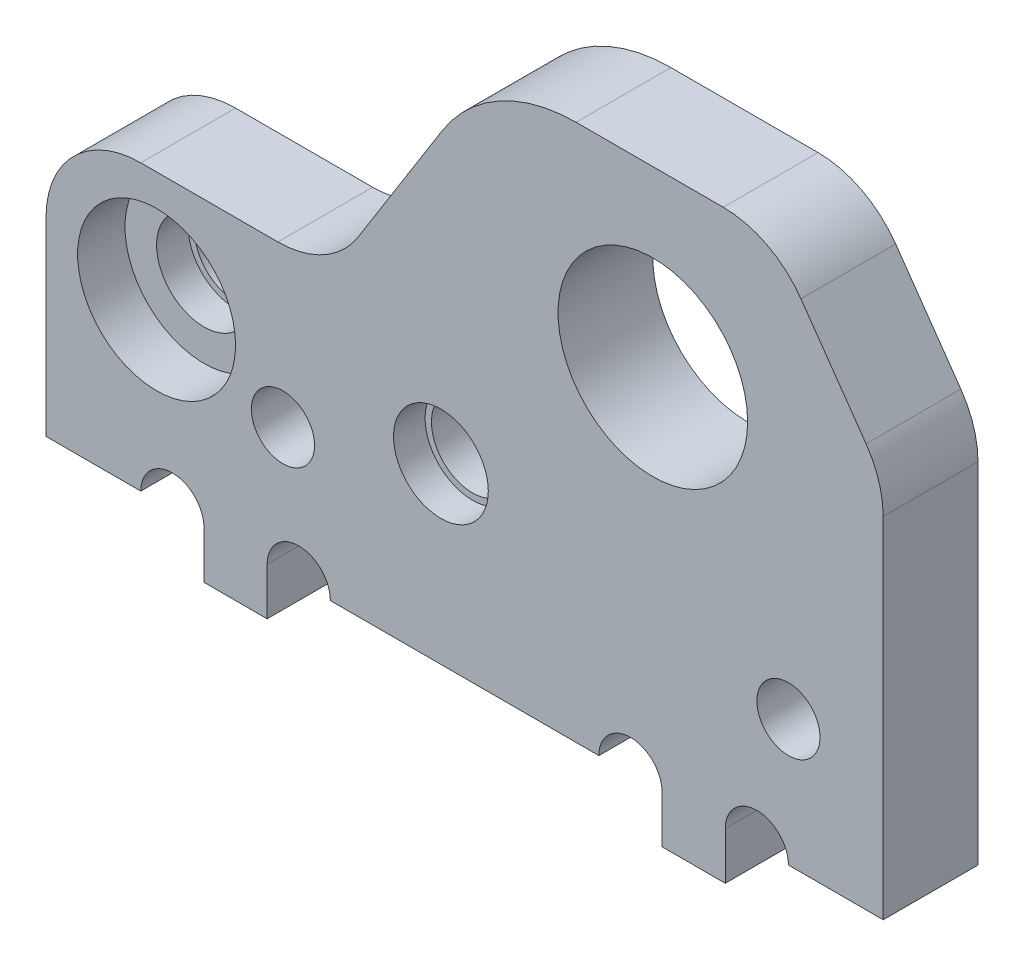
SolidWorks part; units mm, degrees
ref_plane "Front Plane" through (0, 0, 0) normal (0, 0, 1) x (1, 0, 0)
ref_plane "Top Plane" through (0, 0, 0) normal (0, 1, 0) x (1, 0, 0)
ref_plane "Right Plane" through (0, 0, 0) normal (1, 0, 0) x (0, 0, -1)
sketch "Sketch1" plane through (0, 0, 0) normal (0, 1, 0) x (1, 0, 0)
  line L1 (0, 0) -> (26.5, 0)
  line L2 (0, 0) -> (0, 6)
  line L3 (0, 6) -> (26.5, 6)
  line L4 (26.5, 0) -> (26.5, 6)
  dimension "D1" = 26.5
  dimension "D2" = 6
extrude "Boss-Extrude1" add sketch "Sketch1" along normal blind 17
ref_plane "Plane1" through (0, 5.5, 0) normal (0, 1, 0) x (1, 0, 0)
sketch "Sketch2" plane through (0, 0, 0) normal (0, 0, 1) x (1, 0, 0)
  line L0 (5.225, 5.5) -> (-5.225, 5.5) construction
  line L1 (26.5, 17) -> (26.5, 0) construction
  circle A0 centre (12.5, 5.5) radius 1.5
  circle A1 centre (12.5, 5.5) radius 9 construction
  dimension "D1" = 3
  dimension "D2" = 14
  dimension "D3" = 18
extrude "Cut-Extrude1" cut sketch "Sketch2" against normal blind 1
sketch "Sketch3" plane through (0, 0, -1) normal (0, 0, 1) x (1, 0, 0)
  circle A0 centre (12.5, 5.5) radius 1.3
  circle A1 centre (12.5, 5.5) radius 1.5 construction
  dimension "D1" = 0.2
extrude "Cut-Extrude2" cut sketch "Sketch3" against normal through all
sketch "Sketch4" plane through (0, 0, 0) normal (0, 0, 1) x (1, 0, 0)
  line L0 (5.225, 5.5) -> (-5.225, 5.5) construction
  circle A0 centre (19.2082, 11.5) radius 3
  circle A1 centre (12.5, 5.5) radius 1.5 construction
  dimension "D1" = 9
  dimension "D2" = 6
  dimension "D3" = 6
extrude "Cut-Extrude3" cut sketch "Sketch4" against normal through all
sketch "Sketch5" plane through (0, 0, 0) normal (0, 0, 1) x (1, 0, 0)
  line L0 (5.225, 5.5) -> (-5.225, 5.5) construction
  circle A0 centre (3.5, 5.5) radius 2.5
  circle A1 centre (12.5, 5.5) radius 1.5 construction
  dimension "D1" = 5
  dimension "D2" = 9
extrude "Cut-Extrude4" cut sketch "Sketch5" against normal blind 1.5
sketch "Sketch6" plane through (0, 0, -1.5) normal (0, 0, 1) x (1, 0, 0)
  circle A0 centre (3.5, 5.5) radius 1.5
  circle A1 centre (3.5, 5.5) radius 2.5 construction
  dimension "D1" = 3
extrude "Cut-Extrude8" cut sketch "Sketch6" against normal blind 1
sketch "Sketch7" plane through (0, 0, -2.5) normal (0, 0, 1) x (1, 0, 0)
  circle A0 centre (3.5, 5.5) radius 1.3
  circle A1 centre (3.5, 5.5) radius 1.5 construction
  dimension "D1" = 0.2
extrude "Cut-Extrude9" cut sketch "Sketch7" against normal through all
ref_plane "Plane2" through (0, 0, -9.3) normal (0, 0, -1) x (-1, 0, 0)
sketch "Sketch8" plane through (0, 0, -6) normal (0, 0, -1) x (-1, 0, 0)
  circle A0 centre (-3.5, 5.5) radius 2.5
  dimension "D1" = 5
extrude "Cut-Extrude10" cut sketch "Sketch8" against normal blind 1
sketch "Sketch9" plane through (0, 0, -5) normal (0, 0, -1) x (-1, 0, 0)
  circle A0 centre (-3.5, 5.5) radius 1.5
  dimension "D1" = 3
extrude "Cut-Extrude11" cut sketch "Sketch9" against normal blind 1
sketch "Sketch10" plane through (0, 0, -6) normal (0, 0, -1) x (-1, 0, 0)
  line L0 (-26.5, 17) -> (0, 17) construction
  circle A0 centre (-19.2082, 11.5) radius 5.5
  circle A1 centre (-19.2082, 11.5) radius 3 construction
  circle A2 centre (-19.2082, 11.5) radius 3
extrude "Boss-Extrude2" add sketch "Sketch10" along normal blind 3.5
sketch "Sketch11" plane through (0, 0, -6) normal (0, 0, -1) x (-1, 0, 0)
  circle A0 centre (-12.5, 5.5) radius 1.3 construction
  circle A1 centre (-12.5, 5.5) radius 1.3
  circle A2 centre (-12.5, 5.5) radius 3
  dimension "D1" = 6
extrude "Boss-Extrude4" add sketch "Sketch11" along normal blind 2
sketch "Sketch12" plane through (0, 0, -8) normal (0, 0, -1) x (-1, 0, 0)
  circle A0 centre (-12.5, 5.5) radius 1.5
  dimension "D1" = 3
extrude "Cut-Extrude12" cut sketch "Sketch12" against normal blind 1
sketch "Sketch17" plane through (0, 0, 0) normal (0, -1, 0) x (1, 0, 0)
  line L0 (10.175, 0) -> (-10.175, 0) construction
  line L1 (5, 0) -> (7, 0)
  line L2 (5, 0) -> (5, -6)
  line L3 (5, -6) -> (7, -6)
  line L4 (7, 0) -> (7, -6)
  line L5 (26.5, -6) -> (0, -6) construction
  line L6 (26.5, 0) -> (26.5, -6) construction
  line L7 (19.5, 0) -> (21.5, 0)
  line L8 (19.5, 0) -> (19.5, -6)
  line L9 (19.5, -6) -> (21.5, -6)
  line L10 (21.5, 0) -> (21.5, -6)
  line L11 (0, -5.236) -> (0, 5.236) construction
  dimension "D1" = 2
  dimension "D2" = 2
  dimension "D3" = 5
  dimension "D4" = 5
extrude "Boss-Extrude6" add sketch "Sketch17" along normal blind 1.5
sketch "Sketch18" plane through (0, 0, -6) normal (0, 0, -1) x (-1, 0, 0)
  line L0 (5.225, 0) -> (-5.225, 0) construction
  line L1 (-21.5, -1.5) -> (-21.5, 0) construction
  line L2 (-19.5, -1.5) -> (-19.5, 0) construction
  line L3 (-7, -1.5) -> (-7, 0) construction
  line L4 (-5, -1.5) -> (-5, 0) construction
  circle A0 centre (-22.5, 0) radius 1
  circle A1 centre (-18.5, 0) radius 1
  circle A2 centre (-8, 0) radius 1
  circle A3 centre (-4, 0) radius 1
  dimension "D1" = 2
extrude "Cut-Extrude17" cut sketch "Sketch18" against normal through all
chamfer "Chamfer2" distance 5 distance2 3.5 1 edges at (26.5, 17, -3)
fillet "Fillet11" radius 3 2 edges at (26.5, 12, -3) (23, 17, -3)
sketch "Sketch19" plane through (0, 0, -6) normal (0, 0, -1) x (-1, 0, 0)
  line L0 (-14.5471, 14.4196) -> (-9.9576, 7.0925)
  line L1 (-13.8002, 2.7964) -> (-21.5918, 6.5434)
  circle A0 centre (-12.5, 5.5) radius 3 construction
  circle A1 centre (-19.2082, 11.5) radius 5.5 construction
  arc A2 (-9.9576, 7.0925) -> (-13.8002, 2.7964) centre (-12.5, 5.5) ccw
  arc A3 (-21.5918, 6.5434) -> (-14.5471, 14.4196) centre (-19.2082, 11.5) ccw
extrude "Boss-Extrude7" add sketch "Sketch19" along normal up to surface (2 mm away) up to face at (11, 5.5, -8)
sketch "Sketch20" plane through (0, 0, -6) normal (0, 0, -1) x (-1, 0, 0)
  line L0 (5.225, 0) -> (-5.225, 0) construction
  line L1 (0, 17) -> (-14.011, 17)
  line L2 (0, 17) -> (0, 9)
  line L3 (0, 9) -> (-9, 9)
  line L5 (-9, 9) -> (-14.011, 17)
  line L6 (-19.2082, 17) -> (0, 17) construction
  line L7 (-9.9576, 7.0925) -> (-14.5471, 14.4196) construction
  dimension "D1" = 9
extrude "Cut-Extrude19" cut sketch "Sketch20" against normal through all
fillet "Fillet13" radius 5 1 edges at (14.011, 17, -3)
fillet "Fillet14" radius 3 1 edges at (9, 9, -3)
fillet "Fillet15" radius 3 1 edges at (0, 9, -3)
sketch "Skizze1" plane through (0, 0, -6) normal (0, 0, -1) x (-1, 0, 0)
  line L0 (3.3, 0) -> (-3.3, 0) construction
  line L1 (-26.5, 11.0543) -> (-26.5, 0) construction
  circle A0 centre (-23.5, 4) radius 1
  circle A1 centre (-7.5, 4) radius 1
  dimension "D1" = 2
  dimension "D2" = 2
  dimension "D3" = 4
  dimension "D4" = 16
  dimension "D5" = 3
extrude "Schnitt-Linear austragen1" cut sketch "Skizze1" against normal through all
ref_plane "Ebene1" through (0, 0, -3) normal (0, 0, -1) x (-1, 0, 0)
sketch "Skizze2" plane through (0, 5.5, 0) normal (0, 1, 0) x (1, 0, 0)
  line L0 (10.175, 3) -> (-10.175, 3) construction
  line L1 (26.5, 9.5) -> (0, 9.5)
  line L2 (26.5, 9.5) -> (26.5, 3)
  line L3 (26.5, 3) -> (0, 3)
  line L4 (0, 9.5) -> (0, 3)
  line L5 (24.7082, 9.5) -> (13.7082, 9.5) construction
  line L6 (26.5, 6) -> (26.5, 0) construction
  line L7 (0, -3.3) -> (0, 3.3) construction
extrude "Schnitt-Linear austragen2" cut sketch "Skizze2" against normal through all both and the other way through all
